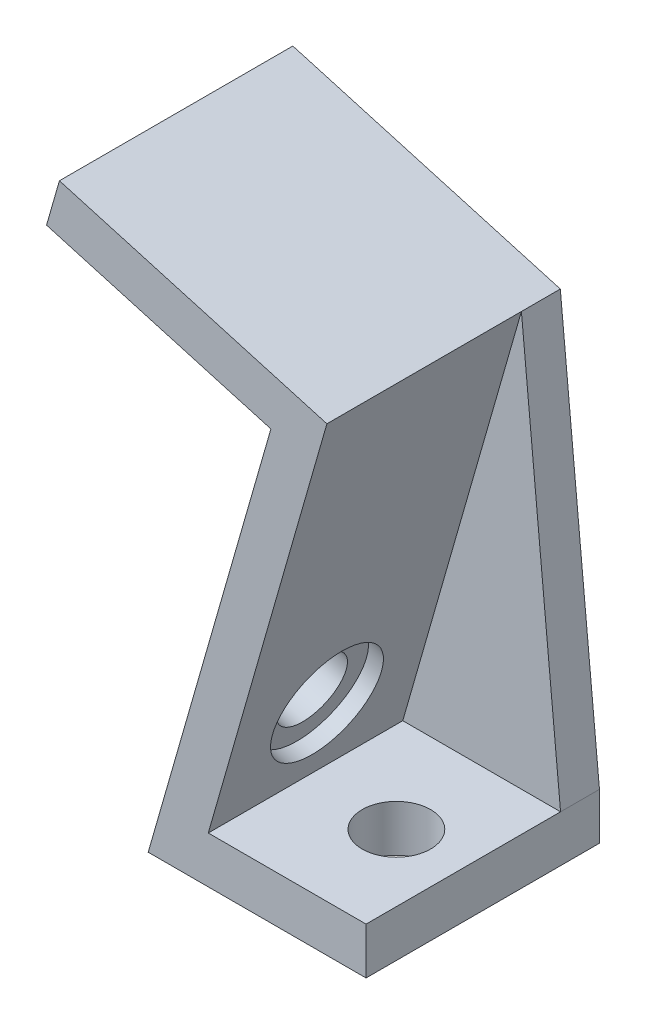
SolidWorks part; units mm, degrees
ref_plane "Płaszczyzna przednia" through (0, 0, 0) normal (0, 0, 1) x (1, 0, 0)
ref_plane "Płaszczyzna górna" through (0, 0, 0) normal (0, 1, 0) x (1, 0, 0)
ref_plane "Płaszczyzna prawa" through (0, 0, 0) normal (1, 0, 0) x (0, 0, -1)
sketch "Szkic2" plane through (0, 0, 0) normal (0, 0, 1) x (1, 0, 0)
  line L0 (-58.6304, 18.2572) -> (-4.4897, 18.2572) construction
  line L1 (-4.4897, -9.2428) -> (-87.0577, -9.2428) construction
  line L2 (-4.4897, 18.2572) -> (-12.3752, -9.2428)
  line L3 (-4.4897, 18.2572) -> (-4.4897, -9.2428) construction
  line L4 (-4.4897, 18.2572) -> (-18.9087, 22.3917)
  line L5 (-12.3752, -9.2428) -> (1.6248, -9.2428)
  line L6 (1.6248, -9.2428) -> (1.6248, -6.2428)
  line L7 (1.6248, -6.2428) -> (-8.515, -6.2428)
  line L8 (-8.515, -6.2428) -> (-0.8908, 20.3461)
  line L9 (-0.8908, 20.3461) -> (-18.0818, 25.2755)
  line L10 (-18.9087, 22.3917) -> (-18.0818, 25.2755)
  line L11 (-1.4897, 18.2572) -> (37.189, 18.2572) construction
  circle A0 centre (-12.3752, -9.2428) radius 3 construction
  circle A1 centre (-1.7177, 17.4623) radius 3 construction
  dimension "D6" = 6
  dimension "D7" = 6
  dimension "D1" = 90
  dimension "D2" = 27.5
  dimension "D3" = 15
  dimension "D4" = 14
  dimension "D5" = 3
extrude "Dodanie-wyciągnięcie1" add sketch "Szkic2" along normal blind 15
sketch "Szkic3" plane through (0, 0, 0) normal (0, 0, -1) x (-1, 0, 0)
  line L0 (0.8908, 20.3461) -> (-1.6248, -6.2428)
  line L1 (-1.6248, -6.2428) -> (8.515, -6.2428)
  line L2 (8.515, -6.2428) -> (0.8908, 20.3461)
extrude "Dodanie-wyciągnięcie2" add sketch "Szkic3" against normal blind 2.5
sketch "Szkic4" plane through (0, -6.2428, 0) normal (0, 1, 0) x (1, 0, 0)
  line L0 (1.6248, -8.75) -> (-8.515, -8.75) construction
  line L1 (1.6248, -15) -> (1.6248, -2.5) construction
  line L2 (-8.515, -15) -> (-8.515, -2.5) construction
  line L3 (-2.6752, -8.75) -> (-2.6752, -15.1989) construction
  circle A1 centre (-2.6752, -8.75) radius 2.2
  dimension "D1" = 4.3
extrude "Wytnij-wyciągnięcie1" cut sketch "Szkic4" against normal blind 10
sketch "Szkic5" plane through (-6.214, 1.7818, 0) normal (0.9613, -0.2756, 0) x (0, 0, -1)
  line L0 (-8.75, -8.3481) -> (-8.75, 12.8956) construction
  line L1 (-15, -8.3481) -> (-2.5, -8.3481) construction
  line L2 (-8.75, -3.3481) -> (-15.504, -3.3481) construction
  circle A0 centre (-8.75, -3.3481) radius 2.2
  dimension "D1" = 5
extrude "Wytnij-wyciągnięcie2" cut sketch "Szkic5" against normal blind 10
sketch "Szkic6" plane through (-6.214, 1.7818, 0) normal (0.9613, -0.2756, 0) x (0, 0, -1)
  circle A0 centre (-8.75, -3.3481) radius 3.5
  dimension "D1" = 7
extrude "Wytnij-wyciągnięcie3" cut sketch "Szkic6" against normal blind 1
